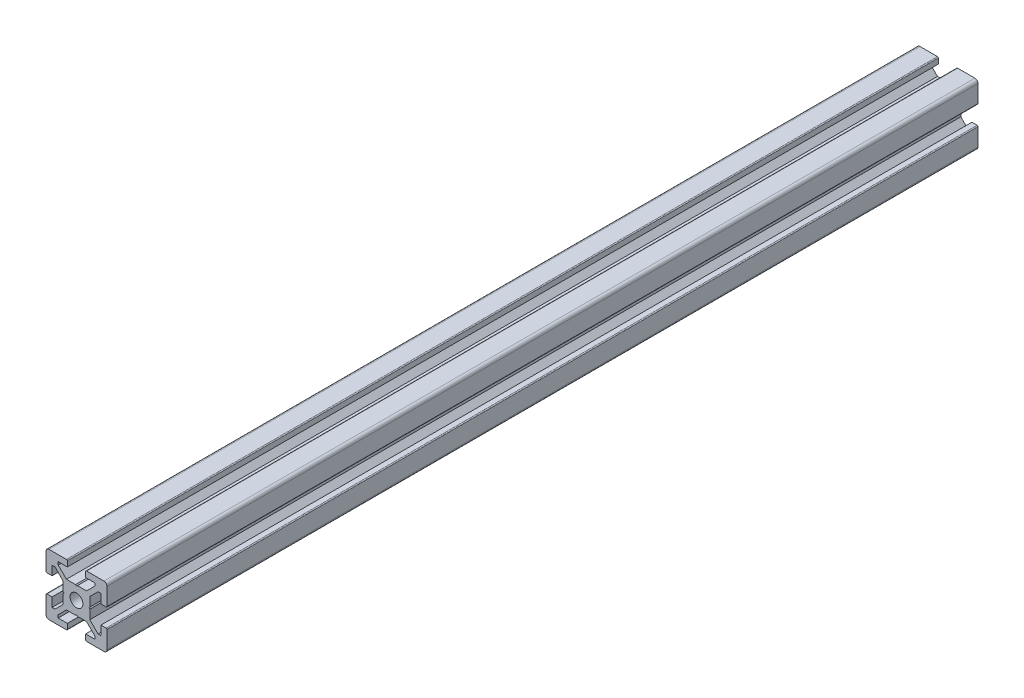
SolidWorks part; units mm, degrees
ref_plane "Front Plane" through (0, 0, 0) normal (0, 0, 1) x (1, 0, 0)
ref_plane "Top Plane" through (0, 0, 0) normal (0, 1, 0) x (1, 0, 0)
ref_plane "Right Plane" through (0, 0, 0) normal (1, 0, 0) x (0, 0, -1)
sketch "Sketch1" plane through (0, 0, 0) normal (0, 0, 1) x (1, 0, 0)
  line L0 (0, 0) -> (0, 4.3607) construction
  line L1 (-10, 10) -> (10, 10) construction
  line L2 (-10, 10) -> (-10, -10) construction
  line L3 (-10, -10) -> (10, -10) construction
  line L4 (10, 10) -> (10, -10) construction
  line L5 (-10, 10) -> (10, -10) construction
  line L6 (-10, -10) -> (10, 10) construction
  line L7 (0, 4.3607) -> (3.3, 4.3607) construction
  line L8 (3.3, 4.3607) -> (6, 7.0607)
  line L9 (6, 7.0607) -> (6, 8)
  line L10 (6, 8) -> (3, 8)
  line L11 (3, 8) -> (3, 9.7)
  line L12 (3.3, 10) -> (9, 10)
  line L13 (0, 4.0607) -> (0.3, 4.3607)
  line L14 (0.3, 4.3607) -> (3.3, 4.3607)
  line L15 (10, 3.3) -> (10, 9)
  line L16 (8, 3) -> (9.7, 3)
  line L17 (8, 6) -> (8, 3)
  line L18 (7.0607, 6) -> (8, 6)
  line L19 (4.3607, 3.3) -> (7.0607, 6)
  line L20 (4.3607, 0.3) -> (4.3607, 3.3)
  line L21 (4.0607, 0) -> (4.3607, 0.3)
  line L22 (4.0607, 0) -> (4.3607, -0.3)
  line L23 (4.3607, -0.3) -> (4.3607, -3.3)
  line L24 (4.3607, -3.3) -> (7.0607, -6)
  line L25 (7.0607, -6) -> (8, -6)
  line L26 (8, -6) -> (8, -3)
  line L27 (8, -3) -> (9.7, -3)
  line L28 (10, -3.3) -> (10, -9)
  line L29 (3.3, -10) -> (9, -10)
  line L30 (3, -8) -> (3, -9.7)
  line L31 (6, -8) -> (3, -8)
  line L32 (6, -7.0607) -> (6, -8)
  line L33 (3.3, -4.3607) -> (6, -7.0607)
  line L34 (0.3, -4.3607) -> (3.3, -4.3607)
  line L35 (0, -4.0607) -> (0.3, -4.3607)
  line L36 (0, -4.0607) -> (-0.3, -4.3607)
  line L37 (-0.3, -4.3607) -> (-3.3, -4.3607)
  line L38 (-3.3, -4.3607) -> (-6, -7.0607)
  line L39 (-6, -7.0607) -> (-6, -8)
  line L40 (-6, -8) -> (-3, -8)
  line L41 (-3, -8) -> (-3, -9.7)
  line L42 (-3.3, -10) -> (-9, -10)
  line L43 (-10, -3.3) -> (-10, -9)
  line L44 (-8, -3) -> (-9.7, -3)
  line L45 (-8, -6) -> (-8, -3)
  line L46 (-7.0607, -6) -> (-8, -6)
  line L47 (-4.3607, -3.3) -> (-7.0607, -6)
  line L48 (-4.3607, -0.3) -> (-4.3607, -3.3)
  line L49 (-4.0607, 0) -> (-4.3607, -0.3)
  line L50 (-4.0607, 0) -> (-4.3607, 0.3)
  line L51 (-4.3607, 0.3) -> (-4.3607, 3.3)
  line L52 (-4.3607, 3.3) -> (-7.0607, 6)
  line L53 (-7.0607, 6) -> (-8, 6)
  line L54 (-8, 6) -> (-8, 3)
  line L55 (-8, 3) -> (-9.7, 3)
  line L56 (-10, 3.3) -> (-10, 9)
  line L57 (-3.3, 10) -> (-9, 10)
  line L58 (-3, 8) -> (-3, 9.7)
  line L59 (-6, 8) -> (-3, 8)
  line L60 (-6, 7.0607) -> (-6, 8)
  line L61 (-3.3, 4.3607) -> (-6, 7.0607)
  line L62 (-0.3, 4.3607) -> (-3.3, 4.3607)
  line L63 (0, 4.0607) -> (-0.3, 4.3607)
  arc A0 (3, 9.7) -> (3.3, 10) centre (3.3, 9.7) cw
  arc A1 (9, 10) -> (10, 9) centre (9, 9) cw
  arc A2 (9.7, 3) -> (10, 3.3) centre (9.7, 3.3) ccw
  arc A3 (9.7, -3) -> (10, -3.3) centre (9.7, -3.3) cw
  arc A4 (10, -9) -> (9, -10) centre (9, -9) cw
  arc A5 (3, -9.7) -> (3.3, -10) centre (3.3, -9.7) ccw
  arc A6 (-3, -9.7) -> (-3.3, -10) centre (-3.3, -9.7) cw
  arc A7 (-9, -10) -> (-10, -9) centre (-9, -9) cw
  arc A8 (-9.7, -3) -> (-10, -3.3) centre (-9.7, -3.3) ccw
  arc A9 (-9.7, 3) -> (-10, 3.3) centre (-9.7, 3.3) cw
  arc A10 (-10, 9) -> (-9, 10) centre (-9, 9) cw
  arc A11 (-3, 9.7) -> (-3.3, 10) centre (-3.3, 9.7) ccw
  circle A12 centre (0, 0) radius 2.1
  point P0 (0, 0)
  point P95 (0, 0)
  dimension "D4" = 1
  dimension "D5" = 0.3
  dimension "D12" = 4.2
  dimension "D1" = 20
  dimension "D2" = 20
  dimension "D3" = 2
  dimension "D6" = 0.75
  dimension "D7" = 3
  dimension "D8" = 0.9393
  dimension "D9" = 3
  dimension "D10" = 0.3
  dimension "D11" = 4
extrude "Boss-Extrude1" add sketch "Sketch1" along normal up to surface (285.5509 mm away)
